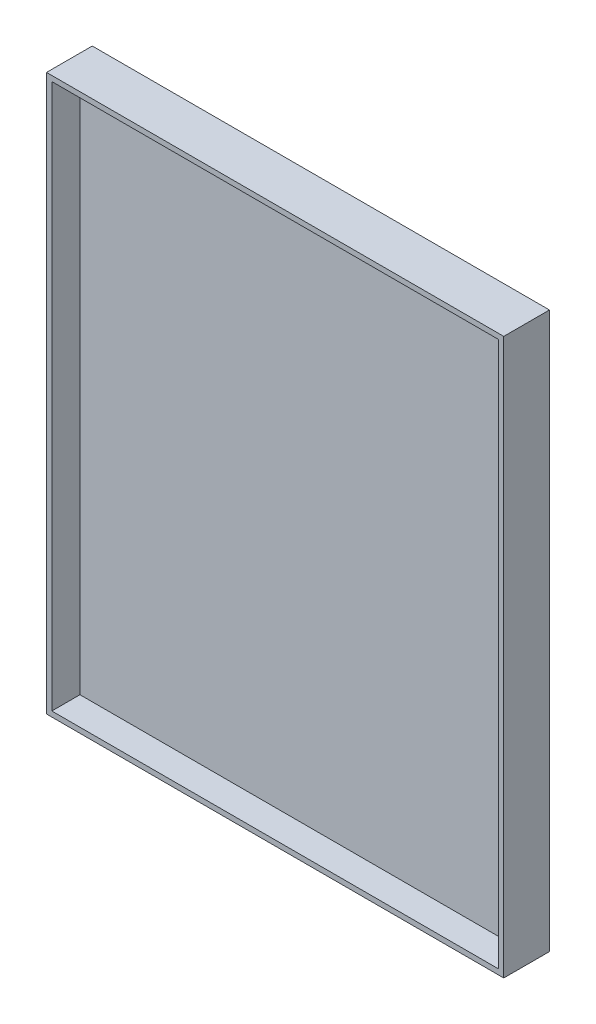
SolidWorks part; units mm, degrees
ref_plane "Alzado" through (0, 0, 0) normal (0, 0, 1) x (1, 0, 0)
ref_plane "Planta" through (0, 0, 0) normal (0, 1, 0) x (1, 0, 0)
ref_plane "Vista lateral" through (0, 0, 0) normal (1, 0, 0) x (0, 0, -1)
sketch "Croquis1" plane through (0, 0, 0) normal (0, 0, 1) x (1, 0, 0)
  line L1 (-65, -79) -> (65, -79)
  line L2 (-65, -79) -> (-65, 79)
  line L3 (-65, 79) -> (65, 79)
  line L4 (65, -79) -> (65, 79)
  line L5 (-65, -79) -> (65, 79) construction
  line L6 (-65, 79) -> (65, -79) construction
  point P0 (0, 0)
  dimension "D1" = 130
  dimension "D2" = 158
extrude "Saliente-Extruir1" add sketch "Croquis1" along normal blind 5
sketch "Croquis2" plane through (0, 0, 5) normal (0, 0, 1) x (1, 0, 0)
  line L1 (-65, -79) -> (65, -79)
  line L2 (-65, -79) -> (-65, 79)
  line L3 (-65, 79) -> (65, 79)
  line L4 (65, -79) -> (65, 79)
  line L5 (-65, -79) -> (65, 79) construction
  line L6 (-65, 79) -> (65, -79) construction
  line L7 (-63.5, -77.5) -> (63.5, -77.5)
  line L8 (-63.5, -77.5) -> (-63.5, 77.5)
  line L9 (-63.5, 77.5) -> (63.5, 77.5)
  line L10 (63.5, -77.5) -> (63.5, 77.5)
  line L11 (-63.5, -77.5) -> (63.5, 77.5) construction
  line L12 (-63.5, 77.5) -> (63.5, -77.5) construction
  point P0 (0, 0)
  point P7 (0, 0)
  dimension "D1" = 127
  dimension "D2" = 155
extrude "Saliente-Extruir2" add sketch "Croquis2" along normal blind 8
